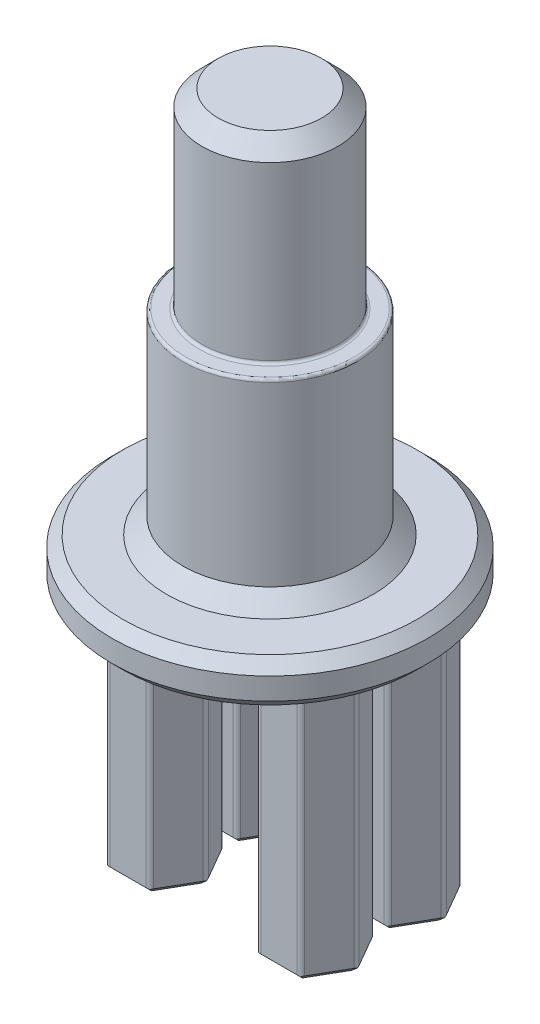
SolidWorks part; units mm, degrees
ref_plane "Front Plane" through (0, 0, 0) normal (0, 0, 1) x (1, 0, 0)
ref_plane "Top Plane" through (0, 0, 0) normal (0, 1, 0) x (1, 0, 0)
ref_plane "Right Plane" through (0, 0, 0) normal (1, 0, 0) x (0, 0, -1)
sketch "Sketch1" plane through (0, 0, 0) normal (0, 1, 0) x (1, 0, 0)
  line L1 (-45.9986, 34.0263) -> (45.9986, 34.0263)
  line L2 (-45.9986, 34.0263) -> (-45.9986, -34.0263)
  line L3 (-45.9986, -34.0263) -> (45.9986, -34.0263)
  line L4 (45.9986, 34.0263) -> (45.9986, -34.0263)
  line L5 (-45.9986, 34.0263) -> (45.9986, -34.0263) construction
  line L6 (-45.9986, -34.0263) -> (45.9986, 34.0263) construction
  point P0 (0, 0)
extrude "Boss-Extrude1" add sketch "Sketch1" along normal blind 8
sketch "Sketch2" plane through (0, 8, 0) normal (0, 1, 0) x (1, 0, 0)
  circle A0 centre (0, 0) radius 16
  dimension "D1" = 32
extrude "Boss-Extrude2" add sketch "Sketch2" along normal blind 36
sketch "Sketch3" plane through (0, 44, 0) normal (0, 1, 0) x (1, 0, 0)
  circle A0 centre (0, 0) radius 12.5
  dimension "D1" = 25
extrude "Boss-Extrude3" add sketch "Sketch3" along normal blind 35
fillet "Fillet1" radius 0.5 1 edges at (0, 44, 12.5)
fillet "Fillet2" radius 0.5 1 edges at (0, 44, 16)
chamfer "Chamfer1" distance 3 angle 45 1 edges at (0, 79, 12.5)
chamfer "Chamfer2" distance 3 angle 45 1 edges at (0, 8, 16)
sketch "Sketch4" plane through (0, 0, 0) normal (0, -1, 0) x (1, 0, 0)
  line L0 (-9.6441, -0.96) -> (-5.747, 5.79)
  line L1 (-8.9224, -2.21) -> (-4.3036, 5.79)
  line L2 (-4.3036, 5.79) -> (-8.9224, 13.79)
  line L3 (-8.9224, 13.79) -> (-18.16, 13.79)
  line L4 (-18.16, 13.79) -> (-22.7788, 5.79)
  line L5 (-22.7788, 5.79) -> (-18.16, -2.21)
  line L6 (-18.16, -2.21) -> (-8.9224, -2.21)
  line L7 (18.7976, -2.21) -> (23.4164, 5.79)
  line L8 (23.4164, 5.79) -> (18.7976, 13.79)
  line L9 (18.7976, 13.79) -> (9.56, 13.79)
  line L10 (9.56, 13.79) -> (4.9412, 5.79)
  line L11 (4.9412, 5.79) -> (9.56, -2.21)
  line L12 (9.56, -2.21) -> (18.7976, -2.21)
  line L13 (-8.9224, -18.21) -> (-4.3036, -10.21)
  line L14 (-4.3036, -10.21) -> (-8.9224, -2.21)
  line L15 (-8.9224, -2.21) -> (-18.16, -2.21)
  line L16 (-18.16, -2.21) -> (-22.7788, -10.21)
  line L17 (-22.7788, -10.21) -> (-18.16, -18.21)
  line L18 (-18.16, -18.21) -> (-8.9224, -18.21)
  line L19 (18.7976, -18.21) -> (23.4164, -10.21)
  line L20 (23.4164, -10.21) -> (18.7976, -2.21)
  line L21 (18.7976, -2.21) -> (9.56, -2.21)
  line L22 (9.56, -2.21) -> (4.9412, -10.21)
  line L23 (4.9412, -10.21) -> (9.56, -18.21)
  line L24 (9.56, -18.21) -> (18.7976, -18.21)
  line L25 (-5.747, 5.79) -> (-9.6441, 12.54)
  line L26 (-9.6441, 12.54) -> (-17.4383, 12.54)
  line L27 (-17.4383, 12.54) -> (-21.3354, 5.79)
  line L28 (-21.3354, 5.79) -> (-17.4383, -0.96)
  line L29 (-17.4383, -0.96) -> (-9.6441, -0.96)
  line L30 (-9.6441, -16.96) -> (-5.747, -10.21)
  line L31 (-5.747, -10.21) -> (-9.6441, -3.46)
  line L32 (-9.6441, -3.46) -> (-17.4383, -3.46)
  line L33 (-17.4383, -3.46) -> (-21.3354, -10.21)
  line L34 (-21.3354, -10.21) -> (-17.4383, -16.96)
  line L35 (-17.4383, -16.96) -> (-9.6441, -16.96)
  line L36 (18.0759, -16.96) -> (21.973, -10.21)
  line L37 (21.973, -10.21) -> (18.0759, -3.46)
  line L38 (18.0759, -3.46) -> (10.2817, -3.46)
  line L39 (10.2817, -3.46) -> (6.3846, -10.21)
  line L40 (6.3846, -10.21) -> (10.2817, -16.96)
  line L41 (10.2817, -16.96) -> (18.0759, -16.96)
  line L42 (18.0759, -0.96) -> (21.973, 5.79)
  line L43 (21.973, 5.79) -> (18.0759, 12.54)
  line L44 (18.0759, 12.54) -> (10.2817, 12.54)
  line L45 (10.2817, 12.54) -> (6.3846, 5.79)
  line L46 (6.3846, 5.79) -> (10.2817, -0.96)
  line L47 (10.2817, -0.96) -> (18.0759, -0.96)
  circle A0 centre (-13.5412, 5.79) radius 8 construction
  circle A1 centre (14.1788, 5.79) radius 8 construction
  circle A2 centre (-13.5412, -10.21) radius 8 construction
  circle A3 centre (14.1788, -10.21) radius 8 construction
  dimension "D3" = 16
  dimension "D1" = 27.72
  dimension "D2" = 16
  dimension "D5" = 18.16
  dimension "D6" = 13.79
  dimension "D4" = 1.25
extrude "Boss-Extrude4" add sketch "Sketch4" along normal blind 48 contours L40 L41 L36 L37 L38 L39 | L46 L47 L42 L43 L44 L45 | L28 L29 L0 L25 L26 L27 | L34 L35 L30 L31 L32 L33
chamfer "Chamfer3" distance 1 angle 45 28 edges at (-13.5412, 0, -16.96) (-7.6955, 0, -13.585) (-7.6955, 0, -6.835) (-13.5412, 0, -3.46) (-19.3869, 0, -6.835) (-19.3869, 0, -13.585) (14.1788, 0, -0.96) (20.0245, 0, 2.415) (20.0245, 0, 9.165) (14.1788, 0, 12.54) (8.3331, 0, 9.165) (8.3331, 0, 2.415) (0, 0, -34.0263) (-45.9986, 0, 0) (0, 0, 34.0263) (45.9986, 0, 0) (14.1788, 0, -16.96) (20.0245, 0, -13.585) (20.0245, 0, -6.835) (14.1788, 0, -3.46) (8.3331, 0, -6.835) (8.3331, 0, -13.585) (-13.5412, 0, -0.96) (-7.6955, 0, 2.415) (-7.6955, 0, 9.165) (-13.5412, 0, 12.54) (-19.3869, 0, 9.165) (-19.3869, 0, 2.415)
chamfer "Chamfer4" distance 1 angle 45 24 edges at (8.3331, -48, 9.165) (14.1788, -48, 12.54) (20.0245, -48, 9.165) (20.0245, -48, 2.415) (14.1788, -48, -0.96) (8.3331, -48, 2.415) (-19.3869, -48, 9.165) (-13.5412, -48, 12.54) (-7.6955, -48, 9.165) (-7.6955, -48, 2.415) (-13.5412, -48, -0.96) (-19.3869, -48, 2.415) (-19.3869, -48, -6.835) (-13.5412, -48, -3.46) (-7.6955, -48, -6.835) (-7.6955, -48, -13.585) (-13.5412, -48, -16.96) (-19.3869, -48, -13.585) (8.3331, -48, -6.835) (14.1788, -48, -3.46) (20.0245, -48, -6.835) (20.0245, -48, -13.585) (14.1788, -48, -16.96) (8.3331, -48, -13.585)
fillet "Fillet4" radius 1 24 edges at (-17.4383, -24, -0.96) (-21.3354, -24, 5.79) (-17.4383, -24, 12.54) (-9.6441, -24, 12.54) (-5.747, -24, 5.79) (-9.6441, -24, -0.96) (6.3846, -24, 5.79) (10.2817, -24, 12.54) (18.0759, -24, 12.54) (21.973, -24, 5.79) (18.0759, -24, -0.96) (10.2817, -24, -0.96) (10.2817, -24, -3.46) (18.0759, -24, -3.46) (21.973, -24, -10.21) (18.0759, -24, -16.96) (10.2817, -24, -16.96) (6.3846, -24, -10.21) (-9.6441, -24, -16.96) (-5.747, -24, -10.21) (-9.6441, -24, -3.46) (-17.4383, -24, -3.46) (-21.3354, -24, -10.21) (-17.4383, -24, -16.96)
sketch "Sketch7" plane through (0, 0, 0) normal (0, -1, 0) x (1, 0, 0)
  circle A5 centre (0, 0) radius 29
  circle A6 centre (0, 0) radius 29
  dimension "D1" = 10
extrude "Cut-Extrude1" cut sketch "Sketch7" against normal blind 40 flip side to cut
chamfer "Chamfer5" distance 2 angle 45 2 edges at (0, 0, -29) (0, 8, 29)
sketch "Sketch8" plane through (0, -48, 0) normal (0, -1, 0) x (1, 0, 0)
  point P0 (14.1788, 5.79)
  point P1 (-13.5412, 5.79)
  point P3 (-13.5412, -10.21)
  point P5 (14.1788, -10.21)
hole_wizard "Ø4.0mm Dowel Hole1" positions "Sketch8" profile "Sketch9" hole size "Ø4.0" standard "ISO"
sketch "Sketch9" plane through (14.1788, -48, 5.79) normal (1, 0, 0) x (0, 0, -1)
  line L0 (0, 0) -> (0, 49.2017)
  line L1 (0, 49.2017) -> (2, 48)
  line L2 (2, 48) -> (2, 0)
  line L5 (2, 0) -> (0, 0)
  line L10 (0, 49.2017) -> (-2, 48) construction
  line L11 (0, -6.35) -> (0, 107.95) construction
  dimension "Hole Dia." = 4
  dimension "Hole Depth" = 48
  dimension "Drill Angle" = 118
